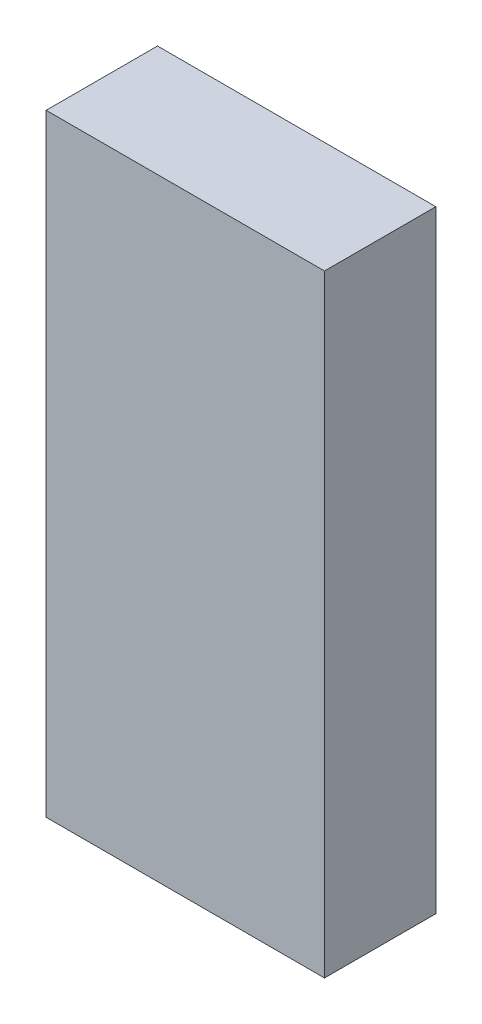
SolidWorks part; units mm, degrees
ref_plane "Plan de face" through (0, 0, 0) normal (0, 0, 1) x (1, 0, 0)
ref_plane "Plan de dessus" through (0, 0, 0) normal (0, 1, 0) x (1, 0, 0)
ref_plane "Plan de droite" through (0, 0, 0) normal (1, 0, 0) x (0, 0, -1)
sketch "Esquisse1" plane through (0, 0, 0) normal (0, 0, 1) x (1, 0, 0)
  line L1 (0, 0) -> (-35, 0)
  line L2 (0, 0) -> (0, 77)
  line L3 (0, 77) -> (-35, 77)
  line L4 (-35, 0) -> (-35, 77)
  dimension "D1" = 77
  dimension "D2" = 35
extrude "Boss.-Extru.1" add sketch "Esquisse1" along normal blind 14
